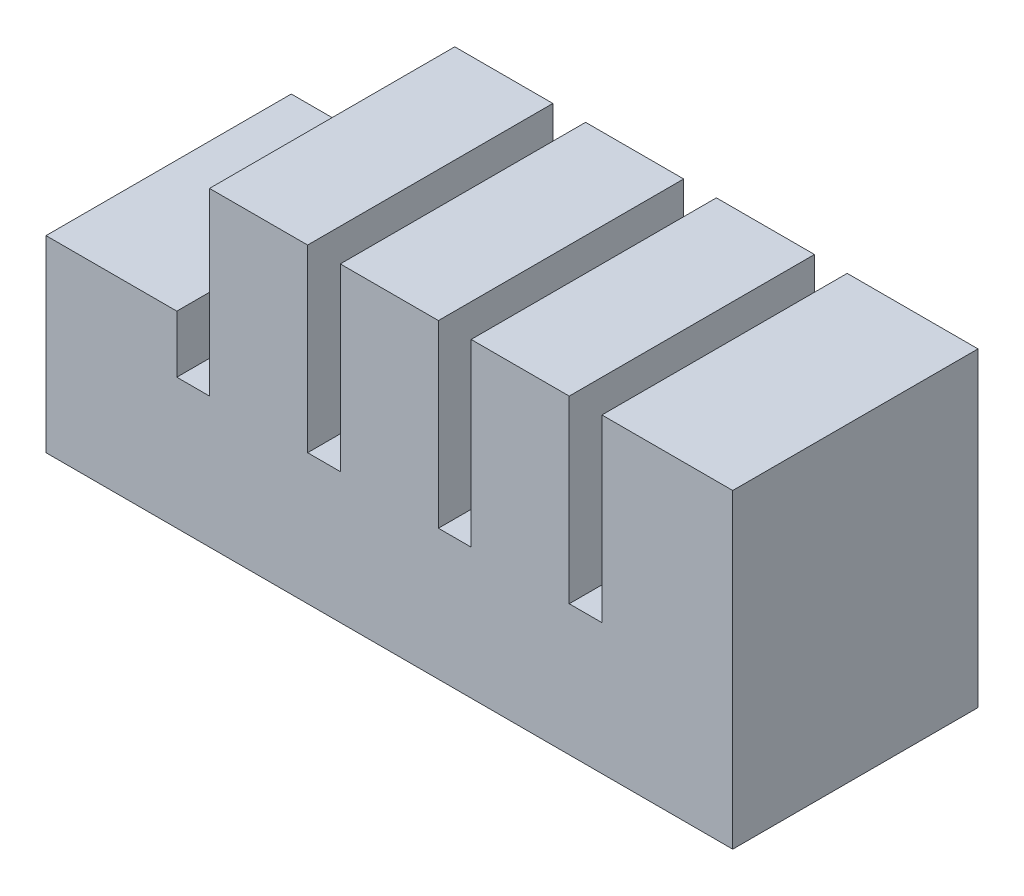
SolidWorks part; units mm, degrees
ref_plane "Front Plane" through (0, 0, 0) normal (0, 0, 1) x (1, 0, 0)
ref_plane "Top Plane" through (0, 0, 0) normal (0, 1, 0) x (1, 0, 0)
ref_plane "Right Plane" through (0, 0, 0) normal (1, 0, 0) x (0, 0, -1)
sketch "Sketch1" plane through (0, 0, 0) normal (0, 1, 0) x (1, 0, 0)
  line L1 (0, 0) -> (6, 0)
  line L2 (0, 0) -> (0, 15)
  line L3 (0, 15) -> (6, 15)
  line L4 (6, 0) -> (6, 15)
extrude "Boss-Extrude1" add sketch "Sketch1" along normal blind 15
sketch "Sketch2" plane through (0, 0, 0) normal (0, -1, 0) x (1, 0, 0)
  line L0 (6, 0) -> (6, -15) construction
  line L1 (5, -2) -> (1, -2)
  line L2 (5, -2) -> (5, -13)
  line L3 (5, -13) -> (1, -13)
  line L4 (1, -2) -> (1, -13)
  line L5 (0, -15) -> (0, 0) construction
  line L6 (0, 0) -> (6, 0) construction
  line L7 (6, -15) -> (0, -15) construction
  dimension "D1" = 1
  dimension "D2" = 1
  dimension "D3" = 2
  dimension "D4" = 2
extrude "Cut-Extrude1" cut sketch "Sketch2" against normal blind 13
sketch "Sketch3" plane through (0, 0, 0) normal (-1, 0, 0) x (0, 0, 1)
  line L0 (0, 15) -> (0, 0) construction
  line L1 (-15, 0) -> (0, 0)
  line L2 (-15, 0) -> (-15, 4)
  line L3 (-15, 4) -> (0, 4)
  line L4 (0, 0) -> (0, 4)
extrude "Boss-Extrude2" add sketch "Sketch3" along normal blind 2
pattern_linear "LPattern1" count 4 spacing 8 along (-1, 0, 0) of "Boss-Extrude2", "Boss-Extrude1", "Cut-Extrude1"
sketch "Sketch4" plane through (-26, 0, 0) normal (-1, 0, 0) x (0, 0, 1)
  line L1 (0, 0) -> (-15, 0)
  line L2 (0, 0) -> (0, 15)
  line L3 (0, 15) -> (-15, 15)
  line L4 (-15, 0) -> (-15, 15)
extrude "Boss-Extrude3" add sketch "Sketch4" along normal blind 8
sketch "Sketch5" plane through (0, 0, 0) normal (0, -1, 0) x (1, 0, 0)
  line L0 (-23, -2) -> (-23, -13) construction
  line L1 (-27, -2) -> (-31, -2)
  line L2 (-27, -2) -> (-27, -13)
  line L3 (-27, -13) -> (-31, -13)
  line L4 (-31, -2) -> (-31, -13)
  line L5 (-34, 0) -> (-18, 0) construction
  dimension "D1" = 4
  dimension "D2" = 2
extrude "Cut-Extrude2" cut sketch "Sketch5" against normal blind 5.5
combine bodies "Combine1" operation type add bodies to combine 104 105 132 103
sketch "Sketch6" plane through (6, 0, 0) normal (1, 0, 0) x (0, 0, -1)
  line L0 (0, 15) -> (15, 15) construction
  line L1 (15, 0) -> (0, 0)
  line L2 (15, 0) -> (15, 15)
  line L3 (15, 15) -> (0, 15)
  line L4 (0, 0) -> (0, 15)
  line L5 (0, 15) -> (0, 0) construction
extrude "Boss-Extrude4" add sketch "Sketch6" along normal blind 2
ref_point "Point1"
sketch "Sketch7" plane through (0, 0, 0) normal (0, -1, 0) x (1, 0, 0)
  line L1 (5, -8.5) -> (-31, -8.5)
  line L2 (5, -8.5) -> (5, -6.5)
  line L3 (5, -6.5) -> (-31, -6.5)
  line L4 (-31, -8.5) -> (-31, -6.5)
  line L5 (5, -8.5) -> (-31, -6.5) construction
  line L6 (5, -6.5) -> (-31, -8.5) construction
  point P0 (-13, -7.5)
extrude "Cut-Extrude3" cut sketch "Sketch7" against normal blind 2
sketch "Sketch8" plane through (0, 15, 0) normal (0, 1, 0) x (1, 0, 0)
  line L1 (-34, 0) -> (-26, 0)
  line L2 (-34, 0) -> (-34, 15)
  line L3 (-34, 15) -> (-26, 15)
  line L4 (-26, 0) -> (-26, 15)
extrude "Cut-Extrude4" cut sketch "Sketch8" against normal blind 7.5
sketch "Sketch9" plane through (0, 0, 0) normal (0, -1, 0) x (1, 0, 0)
  line L1 (8, -15) -> (-34, -15)
  line L2 (8, -15) -> (8, 0)
  line L3 (8, 0) -> (-34, 0)
  line L4 (-34, -15) -> (-34, 0)
extrude "Boss-Extrude5" add sketch "Sketch9" along normal blind 4
